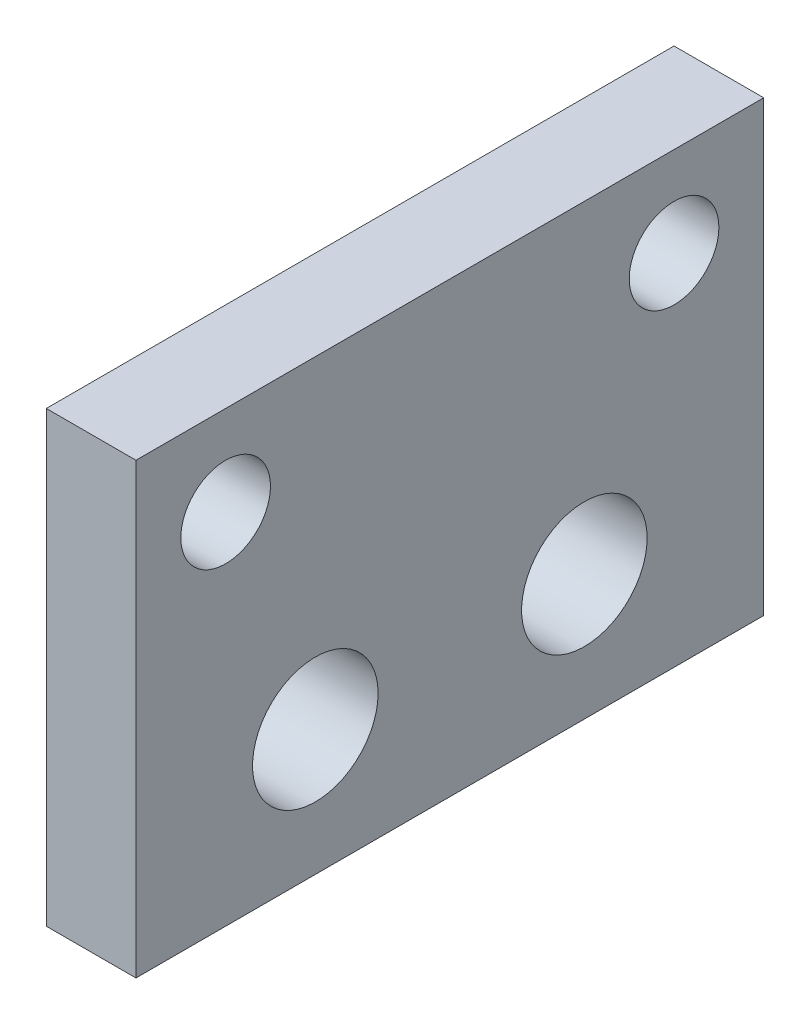
SolidWorks part; units mm, degrees
ref_plane "Front Plane" through (0, 0, 0) normal (0, 0, 1) x (1, 0, 0)
ref_plane "Top Plane" through (0, 0, 0) normal (0, 1, 0) x (1, 0, 0)
ref_plane "Right Plane" through (0, 0, 0) normal (1, 0, 0) x (0, 0, -1)
sketch "Sketch1" plane through (0, 0, 0) normal (1, 0, 0) x (0, 0, -1)
  line L1 (-17.5, 12.5) -> (17.5, 12.5)
  line L2 (-17.5, 12.5) -> (-17.5, -12.5)
  line L3 (-17.5, -12.5) -> (17.5, -12.5)
  line L4 (17.5, 12.5) -> (17.5, -12.5)
  line L5 (-17.5, 12.5) -> (17.5, -12.5) construction
  line L6 (-17.5, -12.5) -> (17.5, 12.5) construction
  point P0 (0, 0)
  dimension "D1" = 35
  dimension "D2" = 25
extrude "Boss-Extrude1" add sketch "Sketch1" along normal blind 5
sketch "Sketch2" plane through (5, 0, 0) normal (1, 0, 0) x (0, 0, -1)
  line L0 (-17.5, 12.5) -> (-17.5, -12.5) construction
  line L1 (17.5, 12.5) -> (-17.5, 12.5) construction
  line L2 (17.5, -12.5) -> (17.5, 12.5) construction
  circle A0 centre (-12.5, 7.5) radius 2.5
  circle A1 centre (12.5, 7.5) radius 2.5
  dimension "D1" = 5
  dimension "D2" = 5
  dimension "D3" = 5
  dimension "D4" = 5
extrude "Cut-Extrude1" cut sketch "Sketch2" against normal through all
sketch "Sketch3" plane through (5, 0, 0) normal (1, 0, 0) x (0, 0, -1)
  line L0 (-17.5, 12.5) -> (-17.5, -12.5) construction
  line L1 (17.5, -12.5) -> (17.5, 12.5) construction
  line L2 (-17.5, -12.5) -> (17.5, -12.5) construction
  circle A0 centre (-7.5, -5.5) radius 3.5
  circle A1 centre (7.5, -5.5) radius 3.5
  point P4 (3.6889, -5.1569)
  dimension "D1" = 7
  dimension "D2" = 10
  dimension "D3" = 10
  dimension "D4" = 7
extrude "Cut-Extrude2" cut sketch "Sketch3" against normal through all
